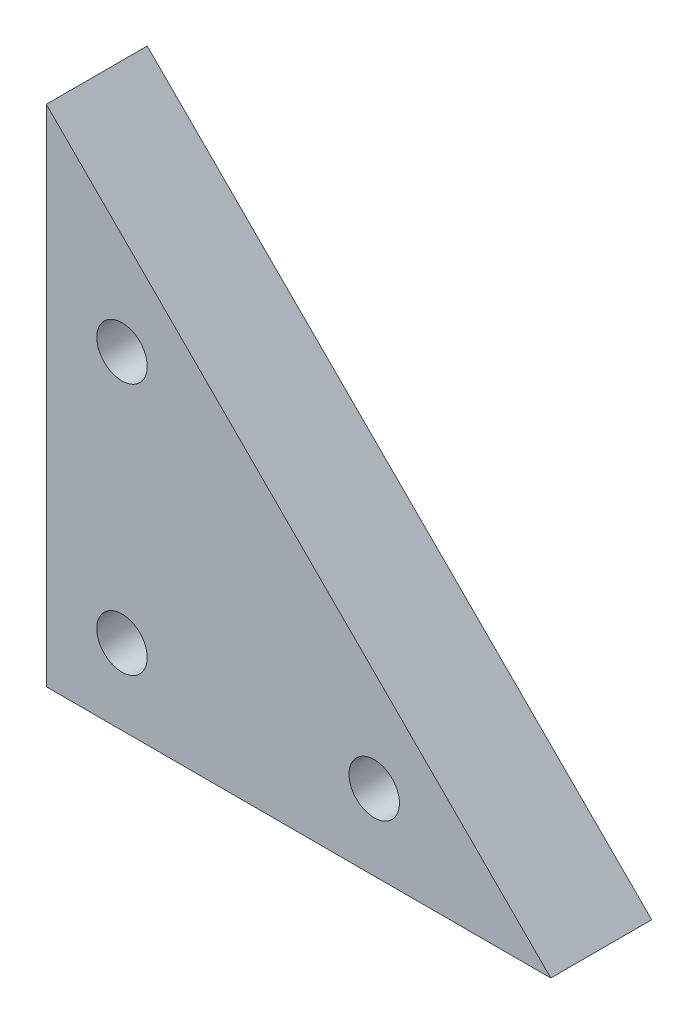
SolidWorks part; units mm, degrees
ref_plane "Front Plane" through (0, 0, 0) normal (0, 0, 1) x (1, 0, 0)
ref_plane "Top Plane" through (0, 0, 0) normal (0, 1, 0) x (1, 0, 0)
ref_plane "Right Plane" through (0, 0, 0) normal (1, 0, 0) x (0, 0, -1)
sketch "Sketch1" plane through (0, 0, 0) normal (0, 0, 1) x (1, 0, 0)
  line L0 (0, 0) -> (100, 0)
  line L1 (100, 0) -> (0, 100)
  line L2 (0, 100) -> (0, 0)
  dimension "D1" = 100
  dimension "D2" = 100
extrude "Boss-Extrude1" add sketch "Sketch1" along normal blind 20
sketch "Sketch2" plane through (0, 0, 20) normal (0, 0, 1) x (1, 0, 0)
  line L0 (0, 100) -> (0, 0) construction
  line L1 (0, 0) -> (100, 0) construction
  circle A0 centre (15, 65) radius 5
  circle A1 centre (15, 15) radius 5
  circle A2 centre (65, 15) radius 5
  dimension "D1" = 10
  dimension "D2" = 10
  dimension "D3" = 10
  dimension "D4" = 15
  dimension "D5" = 15
  dimension "D6" = 50
  dimension "D7" = 50
extrude "Cut-Extrude1" cut sketch "Sketch2" against normal blind 20
